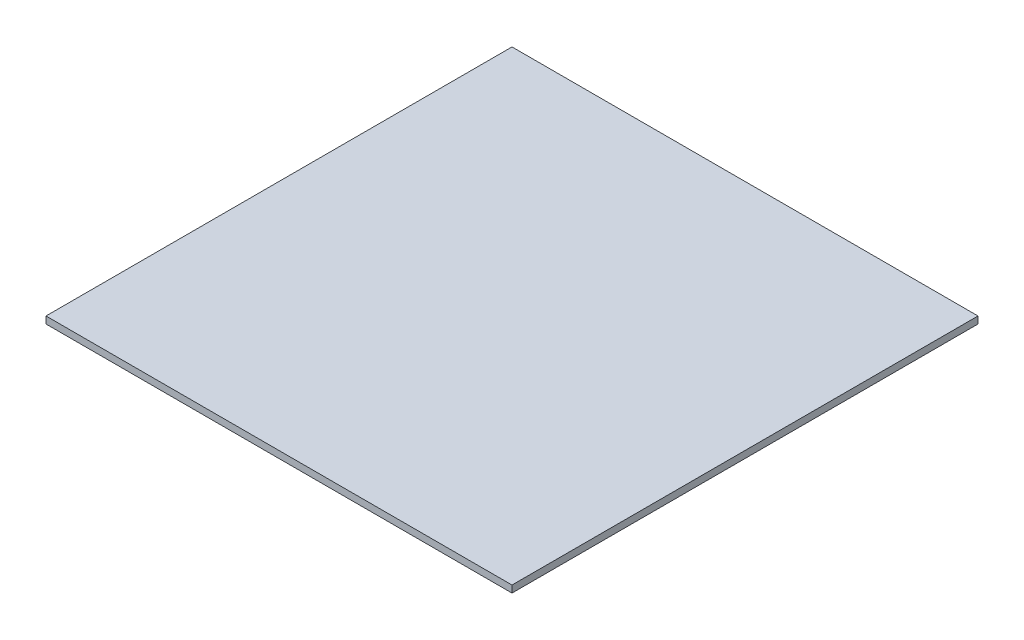
SolidWorks part; units mm, degrees
ref_plane "Front Plane" through (0, 0, 0) normal (0, 0, 1) x (1, 0, 0)
ref_plane "Top Plane" through (0, 0, 0) normal (0, 1, 0) x (1, 0, 0)
ref_plane "Right Plane" through (0, 0, 0) normal (1, 0, 0) x (0, 0, -1)
sketch "Sketch1" plane through (0, 0, 0) normal (0, 1, 0) x (1, 0, 0)
  line L1 (-50, -50) -> (50, -50)
  line L2 (-50, -50) -> (-50, 50)
  line L3 (-50, 50) -> (50, 50)
  line L4 (50, -50) -> (50, 50)
  line L5 (-50, -50) -> (50, 50) construction
  line L6 (-50, 50) -> (50, -50) construction
  point P0 (0, 0)
  dimension "D1" = 100
  dimension "D2" = 100
extrude "Boss-Extrude1" add sketch "Sketch1" along normal blind 1.5
